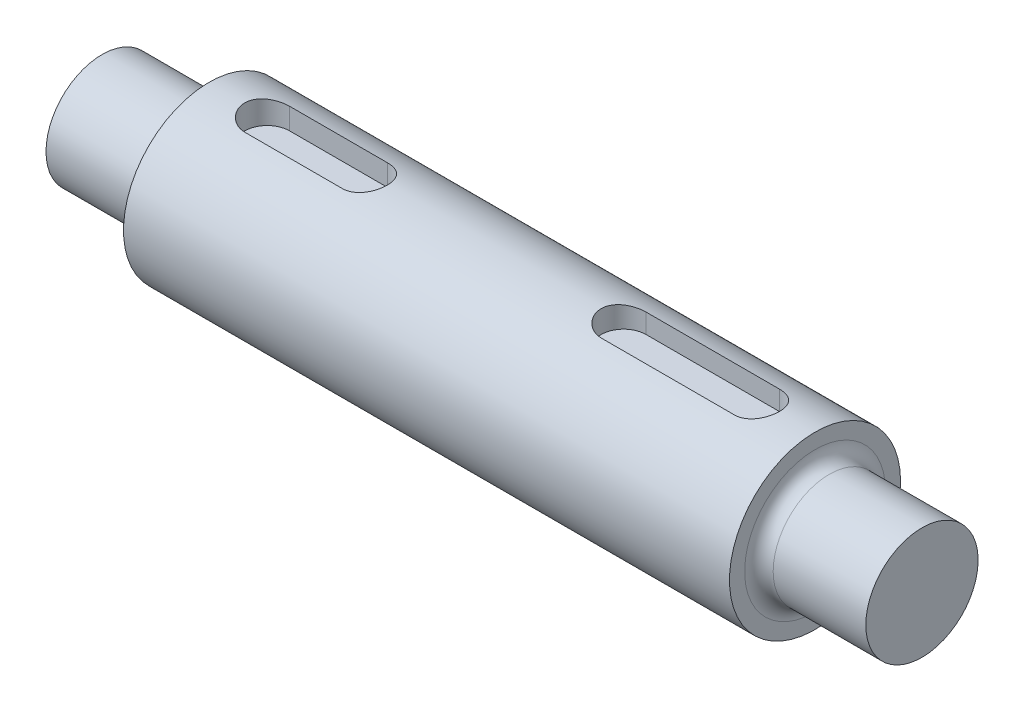
SolidWorks part; units mm, degrees
ref_plane "Front" through (0, 0, 0) normal (0, 0, 1) x (1, 0, 0)
ref_plane "Top" through (0, 0, 0) normal (0, 1, 0) x (1, 0, 0)
ref_plane "Right" through (0, 0, 0) normal (1, 0, 0) x (0, 0, -1)
sketch "Sketch1" plane through (0, 0, 0) normal (1, 0, 0) x (0, 0, -1)
  circle A0 centre (0, 0) radius 20
  dimension "D1" = 40
extrude "Boss-Extrude1" add sketch "Sketch1" along normal blind 38.1
sketch "Sketch2" plane through (38.1, 0, 0) normal (1, 0, 0) x (0, 0, -1)
  circle A0 centre (0, 0) radius 30.48
  dimension "D1" = 60.96
extrude "Boss-Extrude2" add sketch "Sketch2" along normal blind 215.9
sketch "Sketch3" plane through (254, 0, 0) normal (1, 0, 0) x (0, 0, -1)
  circle A0 centre (0, 0) radius 20
  dimension "D1" = 40
extrude "Boss-Extrude3" add sketch "Sketch3" along normal blind 38.1
fillet "Fillet1" radius 5.08 2 edges at (254, 0, -20) (38.1, 0, -20)
ref_plane "Plane1" through (50.8, 0, 0) normal (-1, 0, 0) x (0, 0, 1)
sketch "Sketch6" plane through (50.8, 0, 0) normal (1, 0, 0) x (0, 0, -1)
  line L1 (8.001, 21.812) -> (-8.001, 21.812)
  line L2 (8.001, 21.812) -> (8.001, 37.814)
  line L3 (8.001, 37.814) -> (-8.001, 37.814)
  line L4 (-8.001, 21.812) -> (-8.001, 37.814)
  line L5 (8.001, 21.812) -> (-8.001, 37.814) construction
  line L6 (8.001, 37.814) -> (-8.001, 21.812) construction
  point P0 (0, 29.813)
  dimension "D1" = 16.002
  dimension "D2" = 16.002
  dimension "D3" = 29.813
  dimension "D4" = 0
extrude "Cut-Extrude1" cut sketch "Sketch6" along normal blind 50.8
ref_plane "Plane2" through (177.8, 0, 0) normal (-1, 0, 0) x (0, 0, 1)
sketch "Sketch7" plane through (177.8, 0, 0) normal (-1, 0, 0) x (0, 0, 1)
  line L1 (-8, 38.48) -> (8, 38.48)
  line L2 (-8, 38.48) -> (-8, 22.48)
  line L3 (-8, 22.48) -> (8, 22.48)
  line L4 (8, 38.48) -> (8, 22.48)
  line L5 (-8, 38.48) -> (8, 22.48) construction
  line L6 (-8, 22.48) -> (8, 38.48) construction
  point P0 (0, 30.48)
  dimension "D1" = 16
  dimension "D2" = 16
  dimension "D3" = 30.48
extrude "Cut-Extrude2" cut sketch "Sketch7" against normal blind 63.5
sketch "Sketch8" plane through (0, 21.812, 0) normal (0, 1, 0) x (1, 0, 0)
  line L0 (101.6, 0) -> (101.6, 8.001) construction
  line L1 (101.6, 8.001) -> (93.599, 8.001) construction
  line L2 (93.599, -8.001) -> (101.6, -8.001) construction
  line L3 (50.8, -8.001) -> (58.801, -8.001) construction
  line L4 (50.8, 8.001) -> (50.8, -8.001)
  line L5 (50.8, -8.001) -> (101.6, -8.001)
  line L6 (101.6, -8.001) -> (101.6, 8.001)
  line L7 (101.6, 8.001) -> (50.8, 8.001)
  line L8 (50.8, 8.001) -> (50.8, 0) construction
  line L9 (58.801, -8.001) -> (93.599, -8.001)
  line L10 (101.6, -8.001) -> (101.6, 0) construction
  line L11 (93.599, 8.001) -> (58.801, 8.001)
  line L12 (50.8, 0) -> (50.8, -8.001) construction
  line L13 (58.801, 8.001) -> (50.8, 8.001) construction
  arc A0 (58.801, 8.001) -> (58.801, -8.001) centre (58.801, 0) ccw
  arc A1 (93.599, -8.001) -> (93.599, 8.001) centre (93.599, 0) ccw
  arc A2 (58.801, -8.001) -> (58.801, 8.001) centre (58.801, 0) ccw construction
  arc A3 (93.599, 8.001) -> (93.599, -8.001) centre (93.599, 0) ccw construction
  line M7 (50.8, 8.001) -> (50.8, -8.001)
  line M8 (50.8, -8.001) -> (101.6, -8.001)
  line M9 (101.6, -8.001) -> (101.6, 8.001)
  line M10 (101.6, 8.001) -> (50.8, 8.001)
  dimension "D1" = 0
extrude "Boss-Extrude4" add sketch "Sketch8" along normal up to surface (7.5991 mm away) contours A0 M10 M7 | A0 M7 M8 | A1 M8 M9 | A1 M9 M10
sketch "Sketch10" plane through (0, 22.48, 0) normal (0, 1, 0) x (1, 0, 0)
  line L0 (185.8, 8) -> (177.8, 8)
  line L1 (177.8, 22) -> (177.8, -22) construction
  line L2 (177.8, 8) -> (241.3, 8) construction
  line L3 (177.8, 8) -> (177.8, -8)
  line L4 (177.8, -8) -> (185.8, -8)
  line L5 (233.3, 8) -> (241.3, 8)
  line L6 (241.3, 8) -> (241.3, -8)
  line L7 (241.3, -8) -> (233.3, -8)
  line L10 (185.8, 8) -> (233.3, 8)
  line L11 (233.3, -8) -> (185.8, -8)
  line L12 (185.8, -8) -> (233.3, -8)
  arc A0 (185.8, 8) -> (185.8, -8) centre (185.8, 0) ccw
  arc A1 (233.3, -8) -> (233.3, 8) centre (233.3, 0) ccw
  line M7 (177.8, 8) -> (177.8, -8)
  line M8 (177.8, -8) -> (241.3, -8)
  line M9 (241.3, -8) -> (241.3, 8)
  line M10 (241.3, 8) -> (177.8, 8)
extrude "Boss-Extrude5" add sketch "Sketch10" along normal up to surface (6.9314 mm away) contours A0 M10 M7 | A0 L3 M8 | A1 M8 M9 | A1 L6 M10
